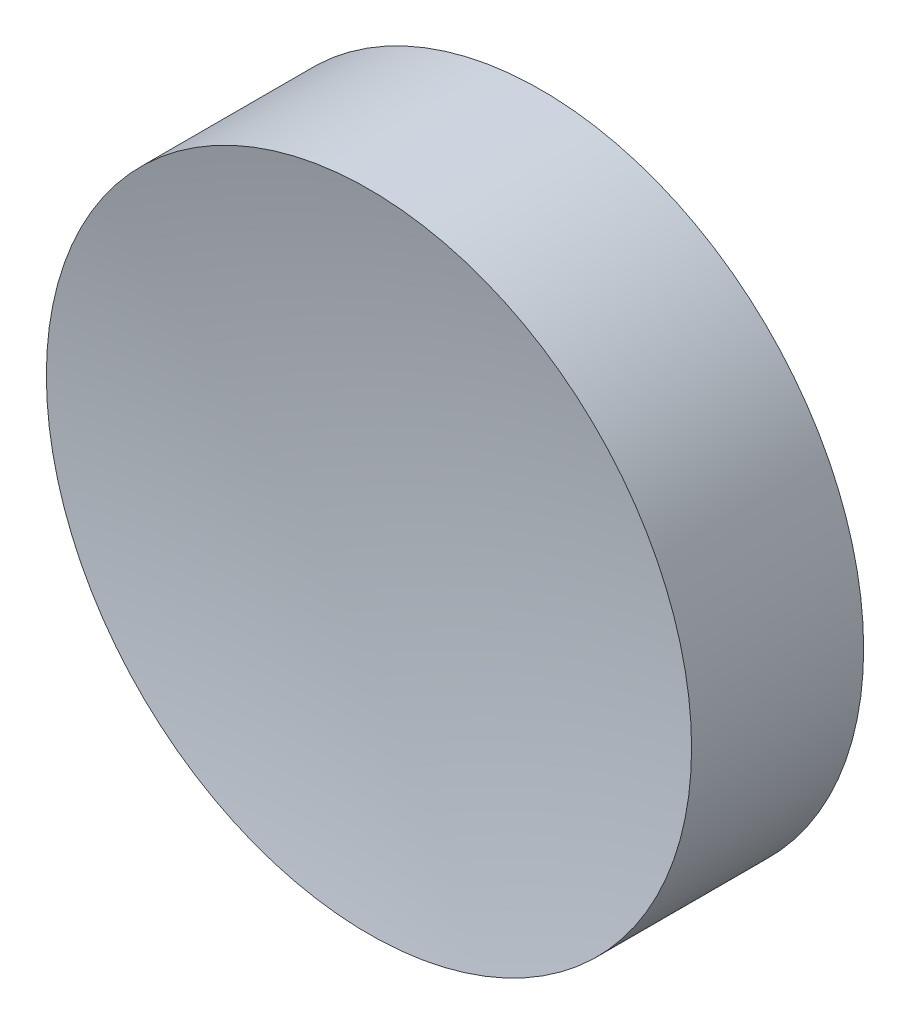
SolidWorks part; units mm, degrees
ref_plane "Front Plane" through (0, 0, 0) normal (0, 0, 1) x (1, 0, 0)
ref_plane "Top Plane" through (0, 0, 0) normal (0, 1, 0) x (1, 0, 0)
ref_plane "Right Plane" through (0, 0, 0) normal (1, 0, 0) x (0, 0, -1)
sketch "Sketch1" plane through (0, 0, 0) normal (0, 0, 1) x (1, 0, 0)
  circle A0 centre (0, 0) radius 30
  dimension "D1" = 60
extrude "Boss-Extrude1" add sketch "Sketch1" along normal blind 16
sketch "Sketch3" plane through (0, 0, 0) normal (0, 1, 0) x (1, 0, 0)
  line L0 (0, -16) -> (30, -16)
  line L1 (0, -12.9694) -> (0, -16)
  arc A1 (0, -12.9694) -> (30, -16) centre (0, -162.9694) cw
revolve "Cut-Revolve2" cut sketch "Sketch3" angle 360 about L1
sketch "Sketch4" plane through (0, 0, 0) normal (0, 0, -1) x (-1, 0, 0)
  circle A0 centre (-16, 0) radius 2.5
extrude "Cut-Extrude2" cut sketch "Sketch4" against normal blind 6
